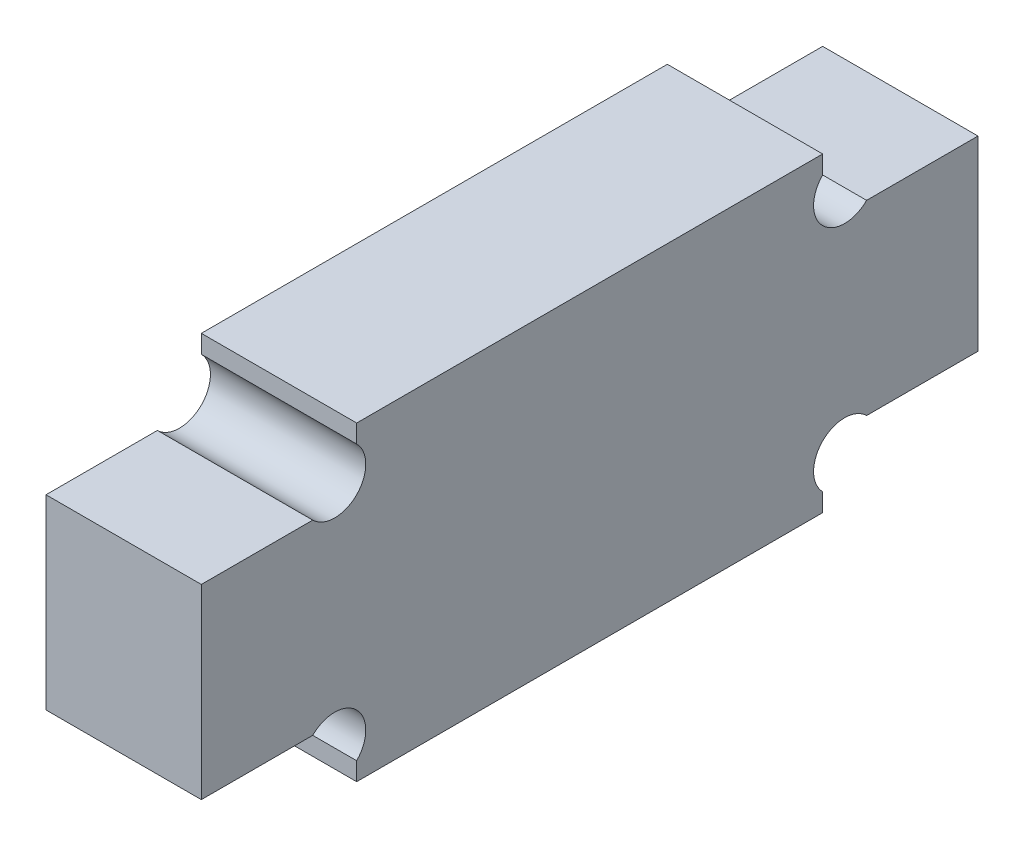
SolidWorks part; units mm, degrees
ref_plane "정면" through (0, 0, 0) normal (0, 0, 1) x (1, 0, 0)
ref_plane "윗면" through (0, 0, 0) normal (0, 1, 0) x (1, 0, 0)
ref_plane "우측면" through (0, 0, 0) normal (1, 0, 0) x (0, 0, -1)
sketch "스케치1" plane through (0, 0, 0) normal (1, 0, 0) x (0, 0, -1)
  line L1 (0, 0) -> (25, 0)
  line L2 (0, 0) -> (0, 10)
  line L3 (0, 10) -> (25, 10)
  line L4 (25, 0) -> (25, 10)
  dimension "D1" = 25
  dimension "D2" = 10
extrude "보스-돌출1" add sketch "스케치1" along normal blind 5
sketch "스케치2" plane through (0, 0, 0) normal (-1, 0, 0) x (0, 0, 1)
  line L1 (-5, 0) -> (0, 0)
  line L2 (-5, 0) -> (-5, 2)
  line L3 (-5, 2) -> (0, 2)
  line L4 (0, 0) -> (0, 2)
  line L5 (0, 0) -> (-25, 0) construction
  line L7 (-25, 10) -> (0, 10) construction
  line L8 (-5, 10) -> (0, 10)
  line L9 (-5, 10) -> (-5, 8)
  line L10 (-5, 8) -> (0, 8)
  line L11 (0, 10) -> (0, 8)
  line L12 (-12.5, 10) -> (-12.5, 0) construction
  line L13 (-25, 10) -> (-25, 8)
  line L14 (-20, 8) -> (-25, 8)
  line L15 (-20, 10) -> (-20, 8)
  line L16 (-20, 10) -> (-25, 10)
  line L17 (-25, 0) -> (-25, 2)
  line L18 (-20, 2) -> (-25, 2)
  line L19 (-20, 0) -> (-20, 2)
  line L20 (-20, 0) -> (-25, 0)
extrude "컷-돌출1" cut sketch "스케치2" against normal blind 10
sketch "스케치4" plane through (0, 0, 0) normal (-1, 0, 0) x (0, 0, 1)
  line L0 (-4.2929, 1.2929) -> (-5, 2) construction
  line L1 (-4.2929, 8.7071) -> (-5, 8) construction
  line L4 (-12.5, 10) -> (-12.5, 0) construction
  line L5 (-20, 10) -> (-5, 10) construction
  line L6 (-5, 0) -> (-20, 0) construction
  line L7 (0, 2) -> (-5, 2) construction
  line L8 (-5, 8) -> (0, 8) construction
  line L9 (-20.7071, 8.7071) -> (-20, 8) construction
  line L10 (-20.7071, 1.2929) -> (-20, 2) construction
  circle A0 centre (-4.2929, 8.7071) radius 1
  circle A1 centre (-4.2929, 1.2929) radius 1
  circle A2 centre (-20.7071, 1.2929) radius 1
  circle A3 centre (-20.7071, 8.7071) radius 1
  dimension "D3" = 2
  dimension "D1" = 45
  dimension "D2" = 45
extrude "컷-돌출2" cut sketch "스케치4" against normal blind 10
